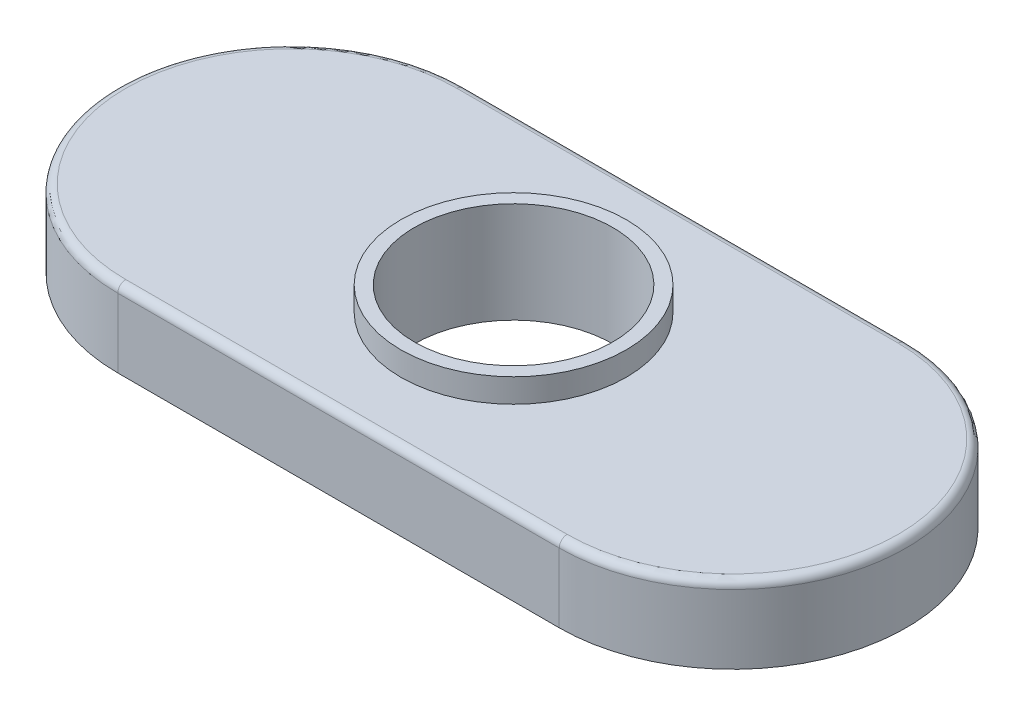
SolidWorks part; units mm, degrees
ref_plane "Front Plane" through (0, 0, 0) normal (0, 0, 1) x (1, 0, 0)
ref_plane "Top Plane" through (0, 0, 0) normal (0, 1, 0) x (1, 0, 0)
ref_plane "Right Plane" through (0, 0, 0) normal (1, 0, 0) x (0, 0, -1)
sketch "Sketch1" plane through (0, 0, 0) normal (0, 1, 0) x (1, 0, 0)
  line L0 (0, 0) -> (14.1224, 0) construction
  line L2 (0, 5.5499) -> (14.1224, 5.5499)
  line L3 (0, -5.5499) -> (14.1224, -5.5499)
  arc A0 (0, 5.5499) -> (0, -5.5499) centre (0, 0) ccw
  arc A1 (14.1224, -5.5499) -> (14.1224, 5.5499) centre (14.1224, 0) ccw
  point P5 (7.0612, 0)
  dimension "D1" = 11.0998
  dimension "D2" = 14.1224
extrude "Boss-Extrude1" add sketch "Sketch1" along normal blind 2.4638
sketch "Sketch2" plane through (0, 2.4638, 0) normal (0, 1, 0) x (1, 0, 0)
  circle A0 centre (7.112, 0) radius 3.6068
  arc A1 (0, 5.5499) -> (0, -5.5499) centre (0, 0) ccw construction
  dimension "D1" = 7.112
extrude "Boss-Extrude3" add sketch "Sketch2" along normal blind 0.762
sketch "Sketch5" plane through (0, 3.2258, 0) normal (0, 1, 0) x (1, 0, 0)
  circle A0 centre (7.112, 0) radius 3.175
extrude "Cut-Extrude2" cut sketch "Sketch5" against normal through all
fillet "Fillet1" radius 0.254 4 edges at (7.0612, 2.4638, -5.5499) (19.6723, 2.4638, 0) (7.0612, 2.4638, 5.5499) (-5.5499, 2.4638, 0)
